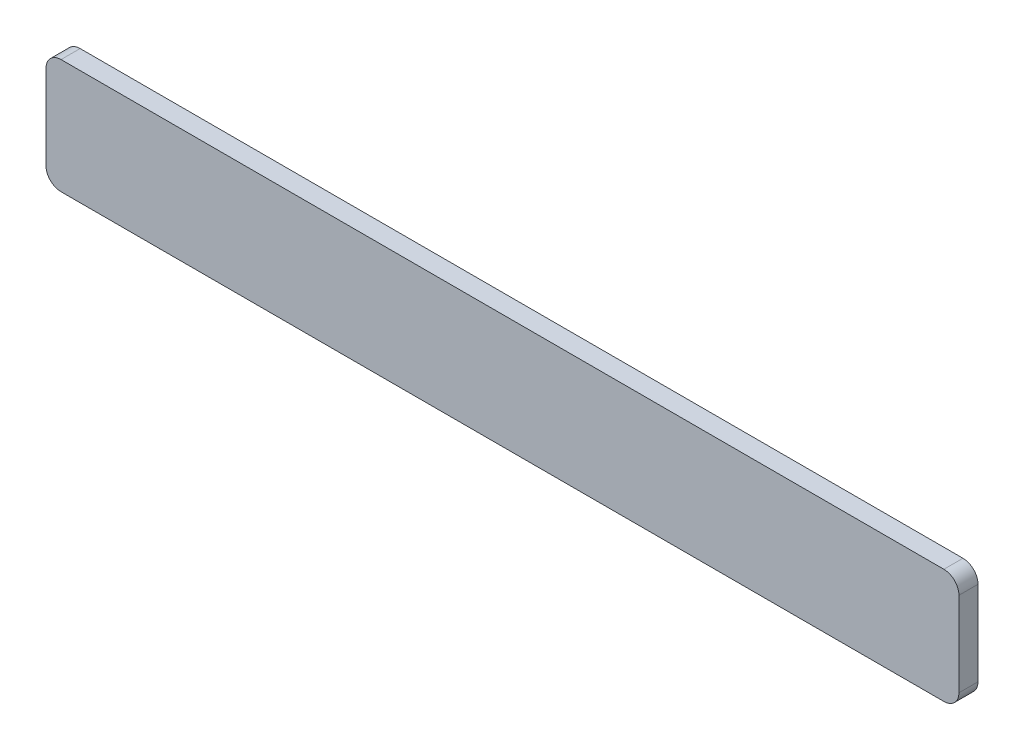
SolidWorks part; units mm, degrees
ref_plane "Front Plane" through (0, 0, 0) normal (0, 0, 1) x (1, 0, 0)
ref_plane "Top Plane" through (0, 0, 0) normal (0, 1, 0) x (1, 0, 0)
ref_plane "Right Plane" through (0, 0, 0) normal (1, 0, 0) x (0, 0, -1)
sketch "Sketch1" plane through (0, 0, 0) normal (0, 0, 1) x (1, 0, 0)
  line L1 (0, 0) -> (-607.57, 0)
  line L2 (0, 0) -> (0, 76.2)
  line L3 (0, 76.2) -> (-607.57, 76.2)
  line L4 (-607.57, 0) -> (-607.57, 76.2)
  dimension "607.57" = 607.57
  dimension "30mm" = 76.2
extrude "Boss-Extrude1" add sketch "Sketch1" along normal blind 12.7 contours L1 L4 L3 L2
fillet "Fillet1" radius 10 4 edges at (-607.57, 0, 6.35) (0, 0, 6.35) (0, 76.2, 6.35) (-607.57, 76.2, 6.35)
